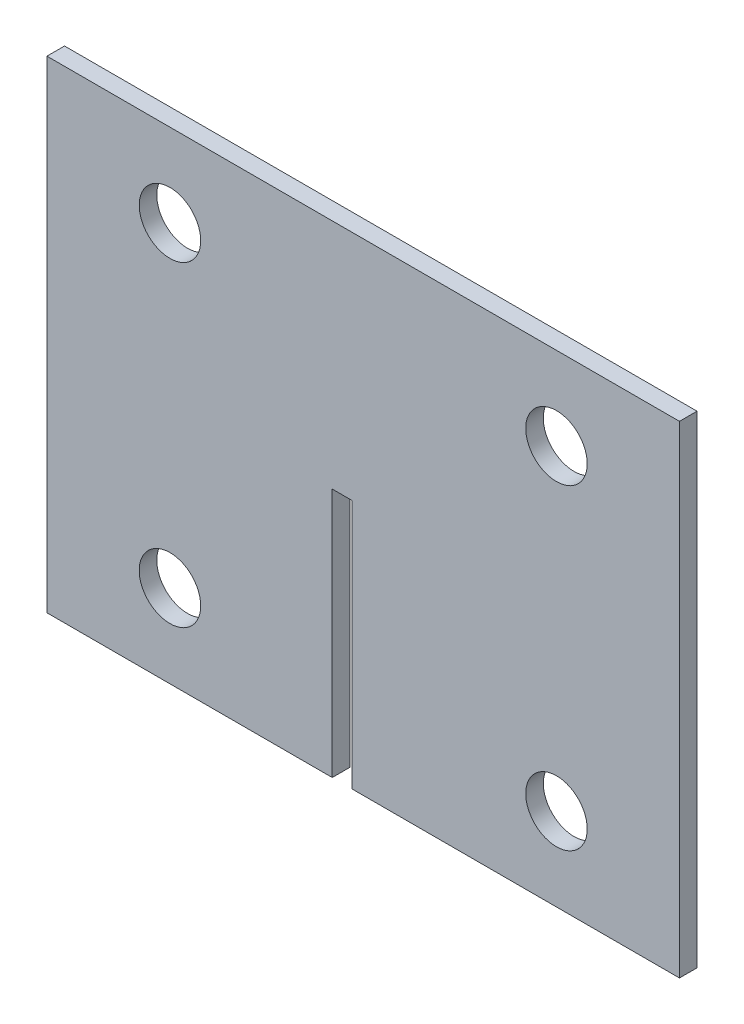
SolidWorks part; units mm, degrees
ref_plane "Front Plane" through (0, 0, 0) normal (0, 0, 1) x (1, 0, 0)
ref_plane "Top Plane" through (0, 0, 0) normal (0, 1, 0) x (1, 0, 0)
ref_plane "Right Plane" through (0, 0, 0) normal (1, 0, 0) x (0, 0, -1)
sketch "Sketch1" plane through (0, 0, 0) normal (0, 0, 1) x (1, 0, 0)
  line L1 (-1647.3727, 226.2156) -> (-1418.7727, 226.2156)
  line L2 (-1647.3727, 226.2156) -> (-1647.3727, 51.9716)
  line L3 (-1647.3727, 51.9716) -> (-1418.7727, 51.9716)
  line L4 (-1418.7727, 226.2156) -> (-1418.7727, 51.9716)
  line L6 (-1558.4727, 39.2716) -> (-1558.4727, 238.9156) construction
  line L7 (-1507.6727, 238.9156) -> (-1507.6727, 39.2716) construction
  point P4 (-1537.5177, 226.2156)
  point P7 (-1537.5177, 51.9716)
  dimension "D1" = 88.9
  dimension "D2" = 88.9
extrude "Boss-Extrude1" add sketch "Sketch1" along normal blind 6.35
sketch "Sketch2" plane through (0, 0, 6.35) normal (0, 0, 1) x (1, 0, 0)
  line L0 (-1507.6727, 139.0936) -> (-1418.7727, 139.0936) construction
  line L2 (-1418.7727, 51.9716) -> (-1418.7727, 226.2156) construction
  line L3 (-1463.2227, 196.2436) -> (-1463.2227, 81.9436) construction
  line L5 (-1647.3727, 139.0936) -> (-1558.4727, 139.0936) construction
  line L6 (-1647.3727, 226.2156) -> (-1647.3727, 51.9716) construction
  line L7 (-1558.4727, 39.2716) -> (-1558.4727, 238.9156) construction
  line L8 (-1602.9227, 196.2436) -> (-1602.9227, 81.9436) construction
  line L9 (-1507.6727, 238.9156) -> (-1507.6727, 39.2716) construction
  circle A0 centre (-1463.2227, 196.2436) radius 11.1125
  circle A1 centre (-1463.2227, 81.9436) radius 11.1125
  circle A2 centre (-1602.9227, 196.2436) radius 11.1125
  circle A3 centre (-1602.9227, 81.9436) radius 11.1125
  point P10 (-1463.2227, 139.0936)
  point P19 (-1602.9227, 139.0936)
  dimension "D2" = 22.225
  dimension "D1" = 114.3
extrude "Cut-Extrude1" cut sketch "Sketch2" against normal up to next
sketch "Sketch3" plane through (0, 0, 6.35) normal (0, 0, 1) x (1, 0, 0)
  line L0 (-1647.3727, 51.9716) -> (-1418.7727, 51.9716) construction
  line L1 (-1544.2646, 142.2686) -> (-1537.1209, 142.2686)
  line L2 (-1544.2646, 142.2686) -> (-1544.2646, 51.9716)
  line L3 (-1544.2646, 51.9716) -> (-1537.1209, 51.9716)
  line L4 (-1537.1209, 142.2686) -> (-1537.1209, 51.9716)
  line L5 (-1540.6927, 226.2156) -> (-1540.6927, 51.9716) construction
  line L6 (-1543.8677, 51.9716) -> (-1537.5177, 51.9716) construction
  line L7 (-1543.8677, 226.2156) -> (-1537.5177, 226.2156) construction
  line L8 (-1537.5177, 51.9716) -> (-1537.5177, 226.2156) construction
  point P12 (-1540.6927, 139.0936)
  point P13 (-1540.6927, 142.2686)
  dimension "D1" = 3.175
  dimension "D2" = 0.3969
extrude "Cut-Extrude2" cut sketch "Sketch3" against normal up to next
